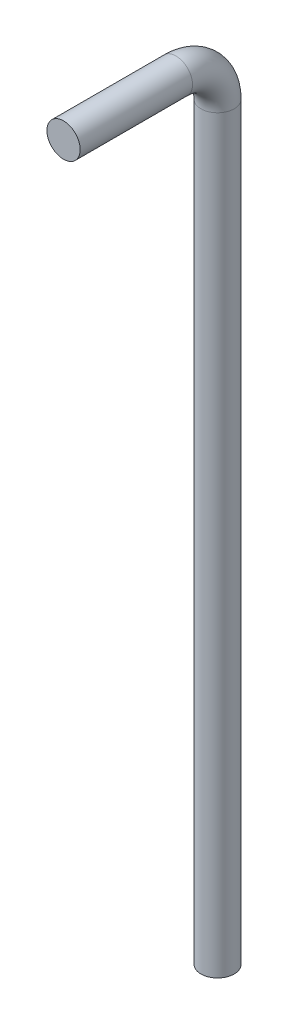
SolidWorks part; units mm, degrees
ref_plane "Front Plane" through (0, 0, 0) normal (0, 0, 1) x (1, 0, 0)
ref_plane "Top Plane" through (0, 0, 0) normal (0, 1, 0) x (1, 0, 0)
ref_plane "Right Plane" through (0, 0, 0) normal (1, 0, 0) x (0, 0, -1)
sketch "Sketch1" plane through (0, 0, 0) normal (0, 1, 0) x (1, 0, 0)
  circle A0 centre (0, 0) radius 5.08
  dimension "D1" = 10.16
sketch "Sketch2" plane through (0, 0, 0) normal (1, 0, 0) x (0, 0, -1)
  line L0 (0, 0) -> (0, 228.6)
  line L1 (-12.7, 241.3) -> (-46.99, 241.3)
  arc A0 (0, 228.6) -> (-12.7, 241.3) centre (-12.7, 228.6) ccw
  point P6 (0, 241.3)
  dimension "D3" = 12.7
  dimension "D1" = 241.3
  dimension "D2" = 46.99
sweep "Sweep1" add profiles "Sketch1" path "Sketch2"
